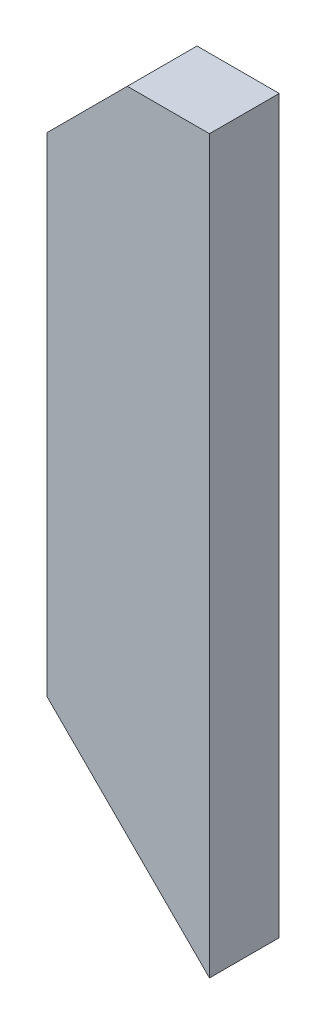
SolidWorks part; units mm, degrees
material "Balsa"
ref_plane "Front Plane" through (0, 0, 0) normal (0, 0, 1) x (1, 0, 0)
ref_plane "Top Plane" through (0, 0, 0) normal (0, 1, 0) x (1, 0, 0)
ref_plane "Right Plane" through (0, 0, 0) normal (1, 0, 0) x (0, 0, -1)
sketch "Sketch1" plane through (0, 0, 0) normal (0, 1, 0) x (1, 0, 0)
  line L1 (-44.45, -19.05) -> (44.45, -19.05)
  line L2 (-44.45, -19.05) -> (-44.45, 19.05)
  line L3 (-44.45, 19.05) -> (44.45, 19.05)
  line L4 (44.45, -19.05) -> (44.45, 19.05)
  line L5 (-44.45, -19.05) -> (44.45, 19.05) construction
  line L6 (-44.45, 19.05) -> (44.45, -19.05) construction
  point P0 (0, 0)
  dimension "D1" = 38.1
  dimension "D2" = 88.9
extrude "Boss-Extrude1" add sketch "Sketch1" along normal blind 444.5
sketch "Sketch2" plane through (0, 0, 19.05) normal (0, 0, 1) x (1, 0, 0)
  line L0 (-44.45, 444.5) -> (44.45, 444.5)
  line L1 (44.45, 444.5) -> (-44.45, 355.6)
  line L2 (-44.45, 444.5) -> (-44.45, 0) construction
  line L3 (-44.45, 355.6) -> (-44.45, 444.5)
  line L4 (44.45, 0) -> (-44.45, 0)
  line L5 (-44.45, 0) -> (-44.45, 88.9)
  line L6 (-44.45, 88.9) -> (44.45, 0)
  dimension "D1" = 45
  dimension "D2" = 45
extrude "Cut-Extrude1" cut sketch "Sketch2" against normal through all
sketch "Sketch3" plane through (0, 0, 19.05) normal (0, 0, 1) x (1, 0, 0)
  line L0 (44.45, 444.5) -> (-0.4513, 399.5987)
  line L1 (-44.45, 355.6) -> (44.45, 444.5) construction
  line L2 (-0.4513, 399.5987) -> (44.45, 399.5987)
  line L3 (44.45, 444.5) -> (44.45, 0) construction
  line L4 (44.45, 399.5987) -> (44.45, 444.5)
  dimension "D1" = 63.5
extrude "Cut-Extrude2" cut sketch "Sketch3" against normal through all
